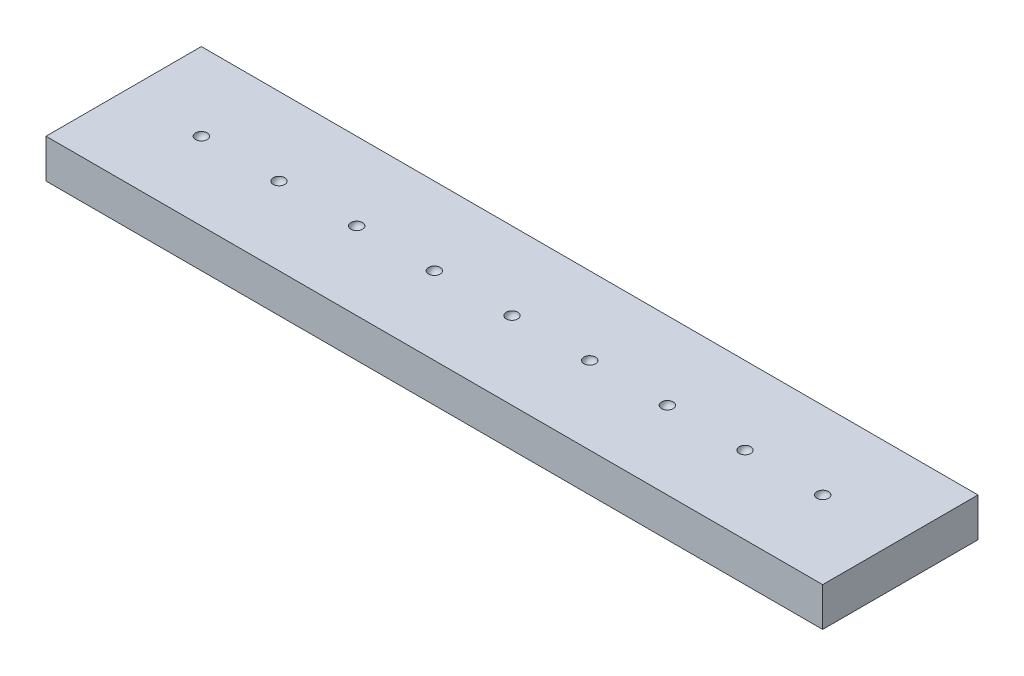
SolidWorks part; units mm, degrees
ref_plane "前视基准面" through (0, 0, 0) normal (0, 0, 1) x (1, 0, 0)
ref_plane "上视基准面" through (0, 0, 0) normal (0, 1, 0) x (1, 0, 0)
ref_plane "右视基准面" through (0, 0, 0) normal (1, 0, 0) x (0, 0, -1)
other "Configuration Table"
sketch "草图1" plane through (0, 0, 0) normal (0, 1, 0) x (1, 0, 0)
  line L1 (0, 0) -> (100, 0)
  line L2 (0, 0) -> (0, 20)
  line L3 (0, 20) -> (100, 20)
  line L4 (100, 0) -> (100, 20)
  dimension "D1" = 100
  dimension "D2" = 20
extrude "凸台-拉伸1" add sketch "草图1" along normal blind 5
sketch "草图2" plane through (0, 5, 0) normal (0, 1, 0) x (1, 0, 0)
  line L0 (0, 10) -> (100, 10) construction
  line L1 (0, 20) -> (0, 0) construction
  line L2 (100, 0) -> (100, 20) construction
  arc A0 (9.25, 10) -> (10.75, 10) centre (10, 10) ccw
  arc A1 (19.25, 10) -> (20.75, 10) centre (20, 10) ccw
  arc A2 (29.25, 10) -> (30.75, 10) centre (30, 10) ccw
  arc A3 (39.25, 10) -> (40.75, 10) centre (40, 10) ccw
  arc A4 (49.25, 10) -> (50.75, 10) centre (50, 10) ccw
  arc A5 (59.25, 10) -> (60.75, 10) centre (60, 10) ccw
  arc A6 (69.25, 10) -> (70.75, 10) centre (70, 10) ccw
  arc A7 (79.25, 10) -> (80.75, 10) centre (80, 10) ccw
  arc A8 (89.25, 10) -> (90.75, 10) centre (90, 10) ccw
  dimension "D1" = 0.75
  dimension "D2" = 10
  dimension "D3" = 1.5
  dimension "D5" = 10
  dimension "D4" = 9
revolve "切除-旋转3" cut sketch "草图2" angle 360 about L0
